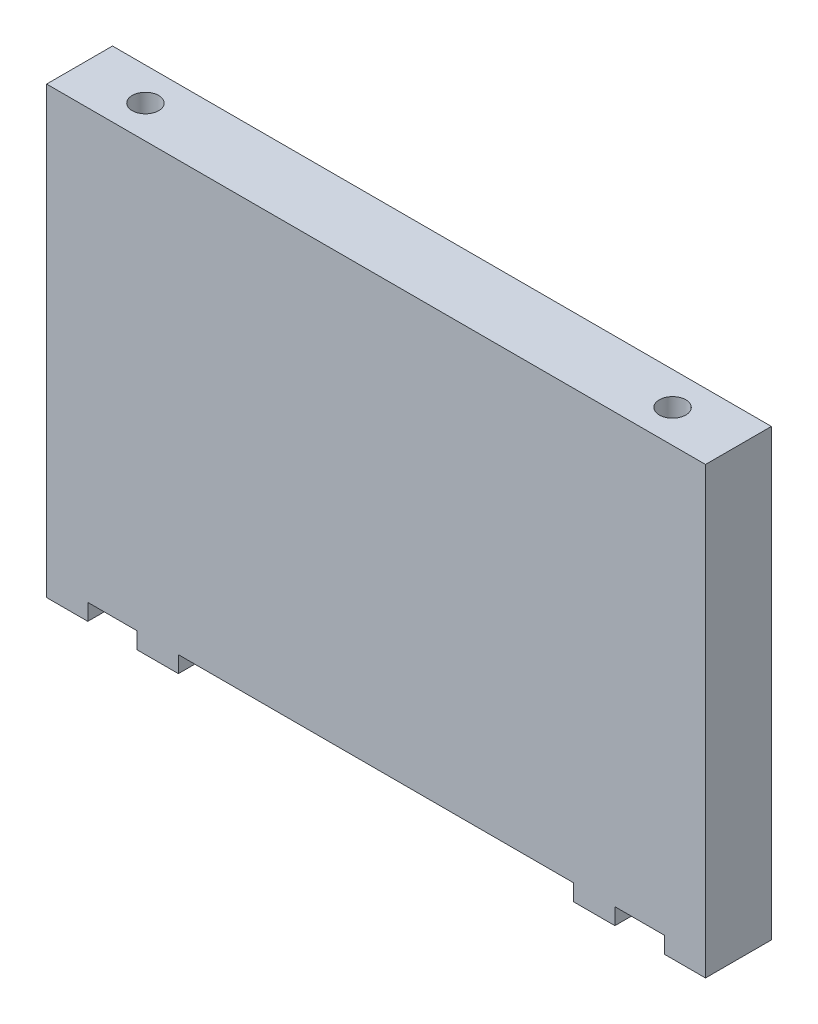
SolidWorks part; units mm, degrees
ref_plane "Front Plane" through (0, 0, 0) normal (0, 0, 1) x (1, 0, 0)
ref_plane "Top Plane" through (0, 0, 0) normal (0, 1, 0) x (1, 0, 0)
ref_plane "Right Plane" through (0, 0, 0) normal (1, 0, 0) x (0, 0, -1)
sketch "Sketch1" plane through (0, 0, 0) normal (0, 0, 1) x (1, 0, 0)
  line L1 (-63.5, 42.8625) -> (63.5, 42.8625)
  line L2 (-63.5, 42.8625) -> (-63.5, -42.8625)
  line L3 (-63.5, -42.8625) -> (63.5, -42.8625)
  line L4 (63.5, 42.8625) -> (63.5, -42.8625)
  line L5 (-63.5, 42.8625) -> (63.5, -42.8625) construction
  line L6 (-63.5, -42.8625) -> (63.5, 42.8625) construction
  point P0 (0, 0)
  dimension "D1" = 127
  dimension "D2" = 85.725
extrude "Boss-Extrude1" add sketch "Sketch1" along normal blind 12.7 contours L2 L3 L4 L1
sketch "Sketch2" plane through (0, 0, 12.7) normal (0, 0, 1) x (1, 0, 0)
  line L0 (-63.5, -42.8625) -> (63.5, -42.8625) construction
  line L1 (-38.1, -42.8625) -> (38.1, -42.8625)
  line L2 (-38.1, -42.8625) -> (-38.1, -39.6875)
  line L3 (-38.1, -39.6875) -> (38.1, -39.6875)
  line L4 (38.1, -42.8625) -> (38.1, -39.6875)
  line L5 (-63.5, 42.8625) -> (63.5, 42.8625) construction
  line L6 (0, 42.8625) -> (0, -42.8625) construction
  point P6 (0, -39.6875)
  dimension "D1" = 76.2
  dimension "D2" = 3.175
extrude "Cut-Extrude1" cut sketch "Sketch2" against normal through all
sketch "Sketch6" plane through (0, -39.6875, 0) normal (0, -1, 0) x (1, 0, 0)
  line L0 (38.1, 12.7) -> (-38.1, 12.7) construction
  line L1 (50.8, 6.35) -> (63.5, 6.35) construction
  line L4 (-50.8, 6.35) -> (-63.5, 6.35) construction
  line L5 (-63.5, 12.7) -> (-63.5, 0) construction
  line L6 (63.5, 12.7) -> (63.5, 0) construction
  line L7 (38.1, 12.7) -> (63.5, 12.7) construction
  point P0 (50.8, 6.35)
  point P1 (-50.8, 6.35)
  dimension "D1" = 6.35
  dimension "D2" = 101.6
sketch "Sketch14" plane through (0, 0, 12.7) normal (0, 0, 1) x (1, 0, 0)
  line L0 (38.1, -42.8625) -> (63.5, -42.8625) construction
  line L1 (46.0375, -42.8625) -> (55.5625, -42.8625)
  line L2 (46.0375, -42.8625) -> (46.0375, -39.6875)
  line L3 (46.0375, -39.6875) -> (55.5625, -39.6875)
  line L4 (55.5625, -42.8625) -> (55.5625, -39.6875)
  line L6 (-63.5, -42.8625) -> (-38.1, -42.8625) construction
  line L7 (-55.5625, -42.8625) -> (-46.0375, -42.8625)
  line L8 (-55.5625, -42.8625) -> (-55.5625, -39.6875)
  line L9 (-55.5625, -39.6875) -> (-46.0375, -39.6875)
  line L10 (-46.0375, -42.8625) -> (-46.0375, -39.6875)
  point P14 (-50.8, -39.6875)
  point P16 (50.8, -39.6875)
  dimension "D1" = 9.525
extrude "Cut-Extrude2" cut sketch "Sketch14" against normal through all
hole_wizard "1/4-20 Tapped Hole1" positions "3DSketch1" profile "Sketch15" tap size "1/4-20" standard "ANSI Inch"
sketch3d "3DSketch1"
  point P0 (-50.8, -39.6875, 6.35)
  point P3 (50.8, -39.6875, 6.35)
sketch "Sketch15" plane through (-50.8, -39.6875, 6.35) normal (1, 0, 0) x (0, 0, -1)
  line L0 (0, 0) -> (0, 18.0438)
  line L1 (0, 18.0438) -> (2.5527, 16.51)
  line L2 (2.5527, 16.51) -> (2.5527, 0)
  line L5 (2.5527, 0) -> (0, 0)
  line L10 (0, 18.0438) -> (-2.5527, 16.51) construction
  line L11 (0, -6.35) -> (0, 107.95) construction
  dimension "Tap Drill Dia." = 5.1054
  dimension "Tap Drill Depth" = 16.51
  dimension "Drill Angle" = 118
cosmetic thread "Hole Thread1" parameters "D1"=12.7, "D2"=6.35
cosmetic thread "Hole Thread2" parameters "D1"=12.7, "D2"=6.35
sketch "Sketch17" plane through (0, 42.8625, 0) normal (0, 1, 0) x (1, 0, 0)
  line L0 (-50.8, -6.35) -> (-63.5, -6.35) construction
  line L1 (-63.5, -12.7) -> (-63.5, 0) construction
  line L4 (50.8, -6.35) -> (63.5, -6.35) construction
  line L5 (63.5, -12.7) -> (63.5, 0) construction
  point P0 (-50.8, -6.35)
  point P1 (50.8, -6.35)
  dimension "D1" = 101.6
hole_wizard "1/4-20 Tapped Hole2" positions "3DSketch3" profile "Sketch18" tap size "1/4-20" standard "ANSI Inch"
sketch3d "3DSketch3"
  point P0 (-50.8, 42.8625, 6.35)
  point P3 (50.8, 42.8625, 6.35)
sketch "Sketch18" plane through (-50.8, 42.8625, 6.35) normal (1, 0, 0) x (0, 0, 1)
  line L0 (0, 0) -> (0, 18.0438)
  line L1 (0, 18.0438) -> (2.5527, 16.51)
  line L2 (2.5527, 16.51) -> (2.5527, 0)
  line L5 (2.5527, 0) -> (0, 0)
  line L10 (0, 18.0438) -> (-2.5527, 16.51) construction
  line L11 (0, -6.35) -> (0, 107.95) construction
  dimension "Tap Drill Dia." = 5.1054
  dimension "Tap Drill Depth" = 16.51
  dimension "Drill Angle" = 118
cosmetic thread "Hole Thread3" parameters "D1"=12.7, "D2"=6.35
cosmetic thread "Hole Thread4" parameters "D1"=12.7, "D2"=6.35
equation "\"D2@Sketch1\"=\"Standoff\""
equation "\"D1@Sketch1\"=\"Length\""
equation "\"D1@Boss-Extrude1\"=\"Thickness\""
equation "\"D1@Sketch2\"=\"Mwidth\""
equation "\"D2@Sketch2\"=\"X\""
equation "\"D1@Sketch6\"=\"Thickness\"/2"
equation "\"D2@Sketch6\"=\"Bolthole\""
